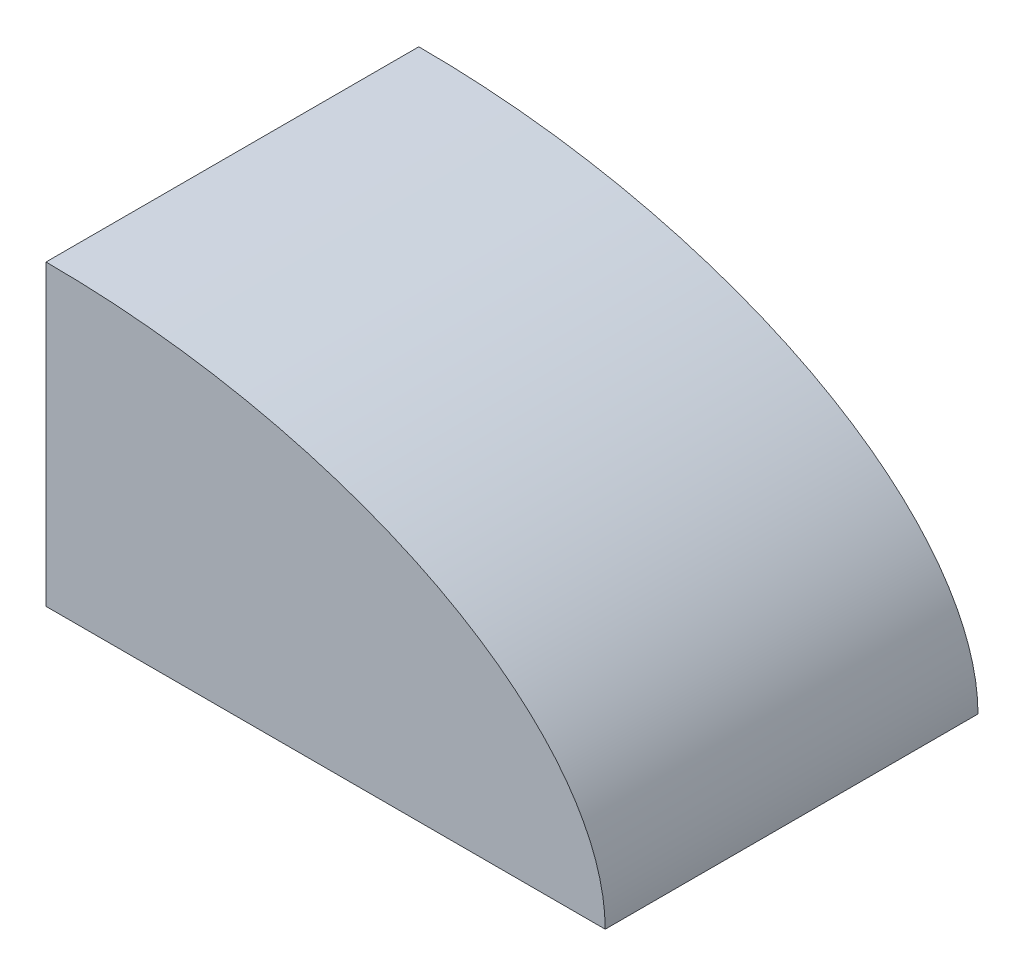
SolidWorks part; units mm, degrees
ref_plane "Front Plane" through (0, 0, 0) normal (0, 0, 1) x (1, 0, 0)
ref_plane "Top Plane" through (0, 0, 0) normal (0, 1, 0) x (1, 0, 0)
ref_plane "Right Plane" through (0, 0, 0) normal (1, 0, 0) x (0, 0, -1)
sketch "Sketch1" plane through (0, 0, 0) normal (0, 0, 1) x (1, 0, 0)
  line L0 (10, 18) -> (10, 10)
  line L1 (10, 10) -> (25, 10)
  ellipse E0 centre (10, 10) end of major axis (25, 10) minor radius 8 (25, 10) -> (10, 18) ccw
extrude "Boss-Extrude1" add sketch "Sketch1" along normal blind 10
